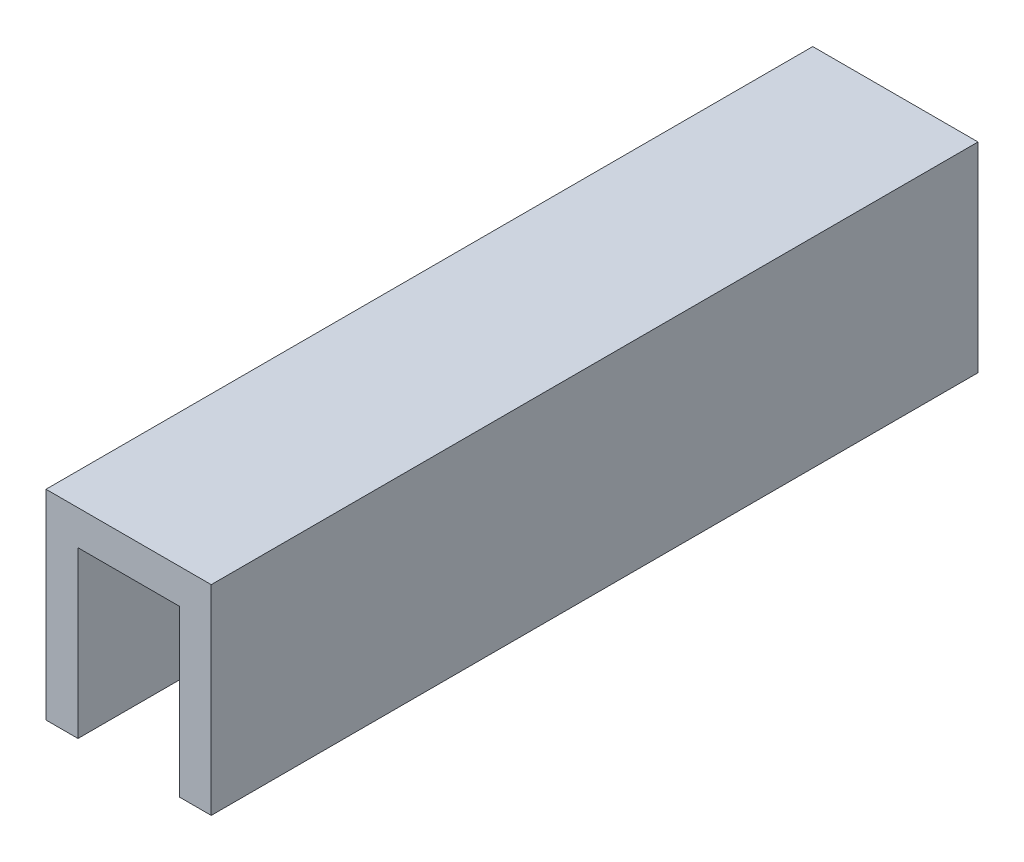
SolidWorks part; units mm, degrees
ref_plane "Front Plane" through (0, 0, 0) normal (0, 0, 1) x (1, 0, 0)
ref_plane "Top Plane" through (0, 0, 0) normal (0, 1, 0) x (1, 0, 0)
ref_plane "Right Plane" through (0, 0, 0) normal (1, 0, 0) x (0, 0, -1)
sketch "Sketch2" plane through (0, 0, 0) normal (0, 0, 1) x (1, 0, 0)
  line L0 (0, 0) -> (4.826, 0)
  line L1 (4.826, 0) -> (4.826, -7.874)
  line L2 (4.826, -7.874) -> (6.35, -7.874)
  line L3 (6.35, -7.874) -> (6.35, 1.651)
  line L5 (-1.524, 1.651) -> (-1.524, -7.874)
  line L6 (-1.524, -7.874) -> (0, -7.874)
  line L7 (0, -7.874) -> (0, 0)
  line L8 (-1.524, 1.651) -> (6.35, 1.651)
  point P3 (7.9271, 1.0228)
  dimension "D1" = 4.826
  dimension "D2" = 7.874
  dimension "D3" = 7.874
  dimension "D4" = 9.525
sketch "Sketch3" plane through (0, 0, 0) normal (1, 0, 0) x (0, 0, -1)
  line L0 (0, 0) -> (-36.5379, 0)
  dimension "D1" = 36.5379
sweep "Sweep3" add profiles "Sketch2" path "Sketch3"
